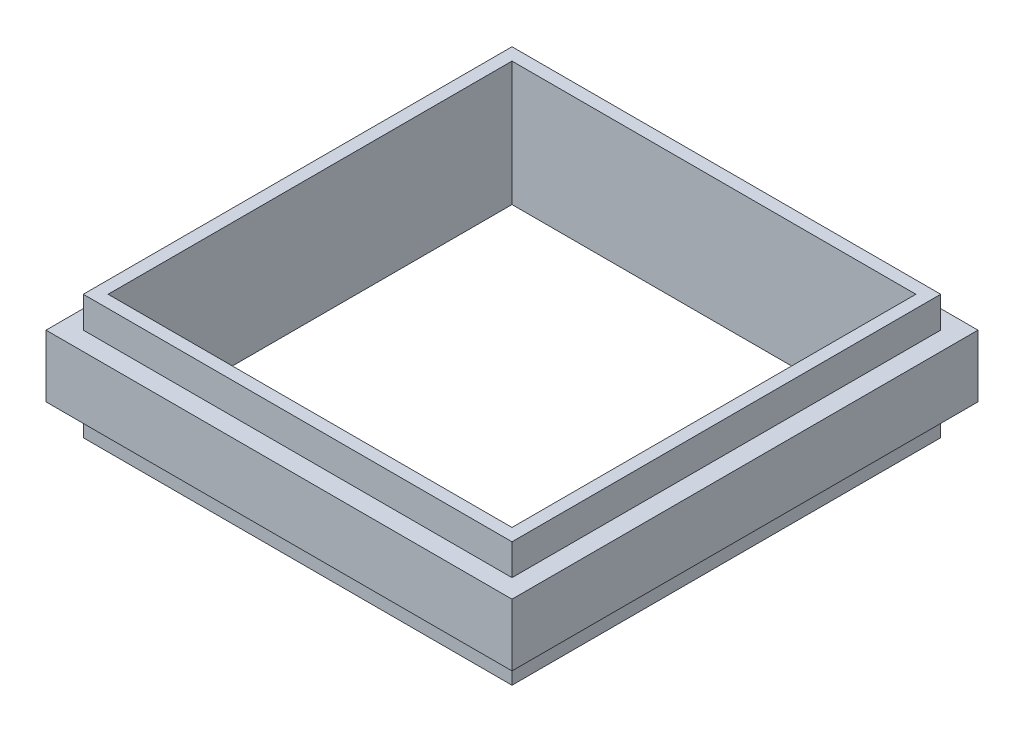
SolidWorks part; units mm, degrees
material "PC Высокая вязкость"
ref_plane "Спереди" through (0, 0, 0) normal (0, 0, 1) x (1, 0, 0)
ref_plane "Сверху" through (0, 0, 0) normal (0, 1, 0) x (1, 0, 0)
ref_plane "Справа" through (0, 0, 0) normal (1, 0, 0) x (0, 0, -1)
sketch "Эскиз1" plane through (0, 0, 0) normal (0, 1, 0) x (1, 0, 0)
  line L1 (-75, -75) -> (75, -75)
  line L2 (-75, -75) -> (-75, 75)
  line L3 (-75, 75) -> (75, 75)
  line L4 (75, -75) -> (75, 75)
  line L5 (-75, -75) -> (75, 75) construction
  line L6 (-75, 75) -> (75, -75) construction
  point P0 (0, 0)
extrude "Бобышка-Вытянуть1" add sketch "Эскиз1" along normal blind 20
sketch "Эскиз2" plane through (0, 20, 0) normal (0, 1, 0) x (1, 0, 0)
  line L1 (-69, -69) -> (69, -69)
  line L2 (-69, -69) -> (-69, 69)
  line L3 (-69, 69) -> (69, 69)
  line L4 (69, -69) -> (69, 69)
  line L5 (-69, -69) -> (69, 69) construction
  line L6 (-69, 69) -> (69, -69) construction
  point P0 (0, 0)
extrude "Бобышка-Вытянуть2" add sketch "Эскиз2" along normal blind 10
sketch "Эскиз3" plane through (0, 0, 0) normal (0, -1, 0) x (-1, 0, 0)
  line L1 (69, 69) -> (-69, 69)
  line L2 (69, 69) -> (69, -69)
  line L3 (69, -69) -> (-69, -69)
  line L4 (-69, 69) -> (-69, -69)
  line L5 (69, 69) -> (-69, -69) construction
  line L6 (69, -69) -> (-69, 69) construction
  point P0 (0, 0)
extrude "Бобышка-Вытянуть3" add sketch "Эскиз3" along normal blind 10
sketch "Эскиз4" plane through (0, 30, 0) normal (0, 1, 0) x (1, 0, 0)
  line L1 (65, 65) -> (-65, 65)
  line L2 (65, 65) -> (65, -65)
  line L3 (65, -65) -> (-65, -65)
  line L4 (-65, 65) -> (-65, -65)
  line L5 (65, 65) -> (-65, -65) construction
  line L6 (65, -65) -> (-65, 65) construction
  point P0 (0, 0)
extrude "Вырез-Вытянуть1" cut sketch "Эскиз4" against normal through all
